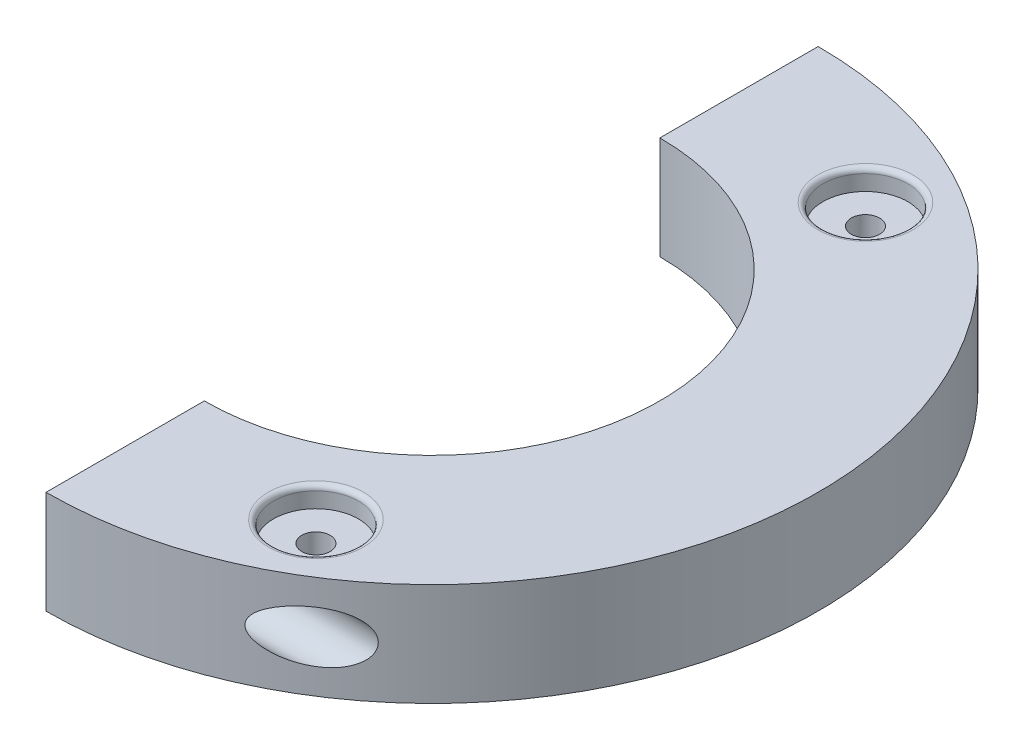
SolidWorks part; units mm, degrees
material "ABS"
ref_plane "Front Plane" through (0, 0, 0) normal (0, 0, 1) x (1, 0, 0)
ref_plane "Top Plane" through (0, 0, 0) normal (0, 1, 0) x (1, 0, 0)
ref_plane "Right Plane" through (0, 0, 0) normal (1, 0, 0) x (0, 0, -1)
sketch "Sketch1" plane through (0, 0, 0) normal (0, 1, 0) x (1, 0, 0)
  line L0 (0, 0) -> (0, 75) construction
  line L1 (0, 0) -> (0, -75) construction
  line L2 (0, 44.25) -> (0, 75)
  line L3 (0, -44.25) -> (0, -75)
  line L6 (50, -75) -> (50, 75) construction
  arc A0 (0, -75) -> (0, 75) centre (0, 0) ccw
  arc A1 (0, 44.25) -> (0, -44.25) centre (0, 0) cw
  circle A2 centre (0, 0) radius 44.25 construction
  point P0 (0, 0)
  dimension "D3" = 88.5
  dimension "D1" = 75
  dimension "D2" = 75
  dimension "D4" = 50
extrude "Boss-Extrude1" add sketch "Sketch1" along normal blind 20
sketch "Sketch2" plane through (0, 0, 0) normal (-1, 0, 0) x (0, 0, 1)
  line L0 (-75, 0) -> (-44.25, 0) construction
  line L1 (-75, 20) -> (-75, 0) construction
  line L2 (44.25, 0) -> (75, 0) construction
  line L3 (75, 20) -> (75, 0) construction
  circle A0 centre (-63, 10) radius 5
  circle A1 centre (63, 10) radius 5
  point P2 (-59.625, 0)
  point P5 (-75, 10)
  point P10 (59.625, 0)
  point P13 (75, 10)
  dimension "D3" = 10
  dimension "D6" = 10
  dimension "D1" = 10
  dimension "D2" = 12
  dimension "D4" = 10
  dimension "D5" = 12
extrude "Cut-Extrude1" cut sketch "Sketch2" against normal blind 150
sketch "Sketch3" plane through (0, 20, 0) normal (0, 1, 0) x (1, 0, 0)
  line L0 (0, 0) -> (110.2982, 0) construction
  line L1 (0, 0) -> (56.9912, 98.7117) construction
  line L3 (0, 0) -> (58.4082, -101.166) construction
  circle A0 centre (0, 0) radius 61.63 construction
  circle A2 centre (30.815, -53.3731) radius 8.25
  circle A3 centre (30.815, 53.3731) radius 8.25
  point P0 (30.815, 53.3731)
  point P7 (30.815, -53.3731)
  dimension "D3" = 123.26
  dimension "D4" = 16.5
  dimension "D5" = 16.5
  dimension "D1" = 60
  dimension "D2" = 60
extrude "Cut-Extrude3" cut sketch "Sketch3" against normal blind 4
sketch "Sketch4" plane through (0, 16, 0) normal (0, 1, 0) x (1, 0, 0)
  line L0 (30.815, 61.6231) -> (30.815, -70.7784) construction
  line L1 (22.565, 53.3731) -> (39.065, 53.3731) construction
  line L2 (22.565, -53.3731) -> (39.065, -53.3731) construction
  circle A0 centre (30.815, 53.3731) radius 8.25 construction
  circle A1 centre (30.815, 53.3731) radius 8.25 construction
  circle A2 centre (30.815, -53.3731) radius 8.25 construction
  circle A3 centre (30.815, -53.3731) radius 8.25 construction
  circle A4 centre (30.815, 53.3731) radius 2.75
  circle A5 centre (30.815, -53.3731) radius 2.75
  point P16 (30.815, 53.3731)
  dimension "D1" = 5.5
  dimension "D2" = 5.5
extrude "Cut-Extrude4" cut sketch "Sketch4" against normal blind 20
sketch "Sketch5" plane through (0, 0, 0) normal (0, -1, 0) x (1, 0, 0)
  line L0 (30.815, 56.1231) -> (30.815, -56.1231) construction
  line L1 (28.065, 53.3731) -> (33.565, 53.3731) construction
  line L2 (28.065, -53.3731) -> (33.565, -53.3731) construction
  circle A0 centre (30.815, 53.3731) radius 2.75 construction
  circle A1 centre (30.815, -53.3731) radius 2.75 construction
  circle A2 centre (30.815, 53.3731) radius 5
  circle A3 centre (30.815, -53.3731) radius 5
  dimension "D1" = 10
  dimension "D2" = 10
extrude "Cut-Extrude5" cut sketch "Sketch5" against normal blind 5
fillet "Fillet1" radius 1 2 edges at (30.815, 20, 61.6231) (30.815, 20, -45.1231)
